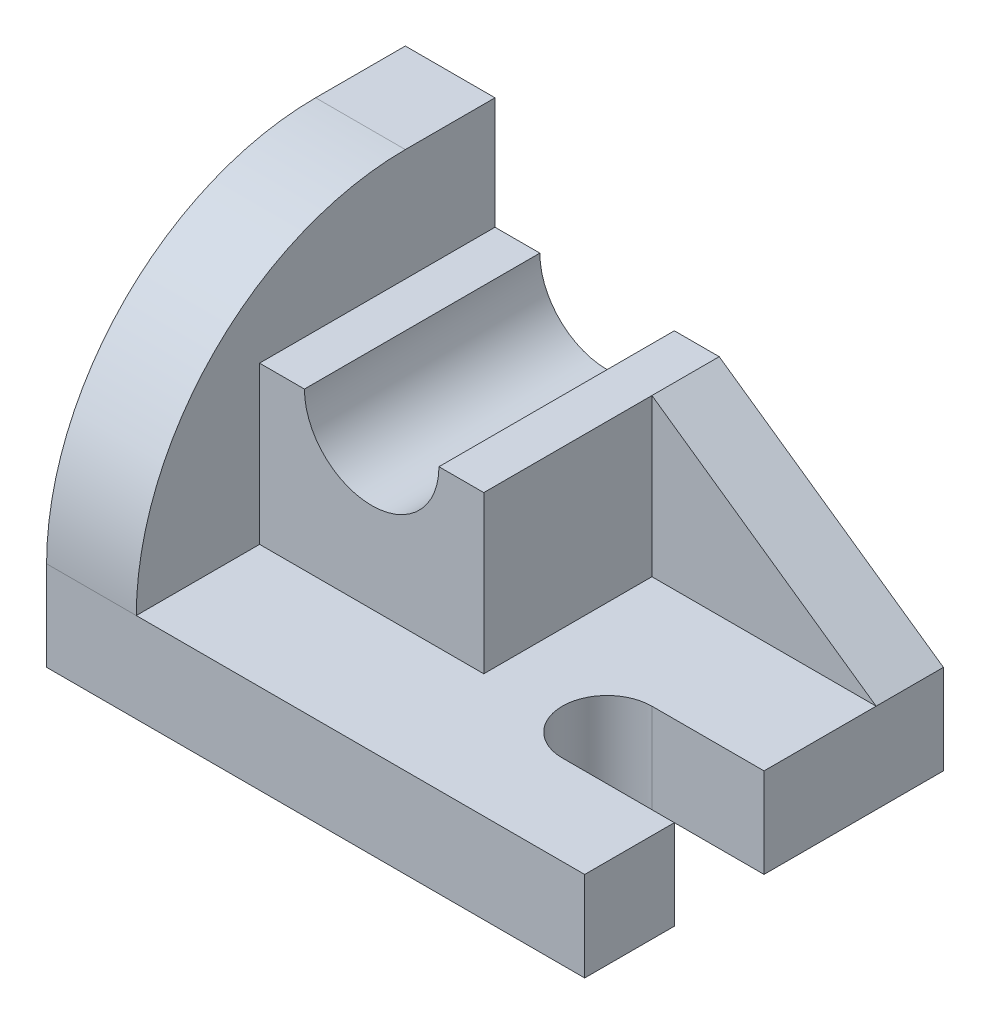
SolidWorks part; units mm, degrees
ref_plane "Front Plane" through (0, 0, 0) normal (0, 0, 1) x (1, 0, 0)
ref_plane "Top Plane" through (0, 0, 0) normal (0, 1, 0) x (1, 0, 0)
ref_plane "Right Plane" through (0, 0, 0) normal (1, 0, 0) x (0, 0, -1)
sketch "Sketch1" plane through (0, 0, 0) normal (0, 1, 0) x (1, 0, 0)
  line L1 (-46.7573, 25.6311) -> (49.2427, 25.6311)
  line L2 (-46.7573, 25.6311) -> (-46.7573, -38.3689)
  line L3 (-46.7573, -38.3689) -> (49.2427, -38.3689)
  line L4 (49.2427, 25.6311) -> (49.2427, -38.3689)
  dimension "D1" = 96
  dimension "D2" = 64
extrude "Boss-Extrude1" add sketch "Sketch1" along normal blind 16
sketch "Sketch2" plane through (0, 16, 0) normal (0, 1, 0) x (1, 0, 0)
  line L0 (-46.7573, -38.3689) -> (49.2427, -38.3689) construction
  line L1 (-46.7573, 25.6311) -> (-30.7573, 25.6311)
  line L2 (-46.7573, 25.6311) -> (-46.7573, -38.3689)
  line L3 (-46.7573, -38.3689) -> (-30.7573, -38.3689)
  line L4 (-30.7573, 25.6311) -> (-30.7573, -38.3689)
  dimension "D1" = 16
extrude "Boss-Extrude2" add sketch "Sketch2" along normal blind 48
fillet "Fillet1" radius 48 1 edges at (-38.7573, 64, 38.3689)
sketch "Sketch3" plane through (0, 16, 0) normal (0, 1, 0) x (1, 0, 0)
  line L0 (49.2427, -6.3689) -> (29.2427, -6.3689)
  line L1 (49.2427, -38.3689) -> (49.2427, 25.6311) construction
  line L2 (49.2427, -22.3689) -> (29.2427, -22.3689)
  line L4 (49.2427, -6.3689) -> (49.2427, -22.3689)
  arc A0 (29.2427, -6.3689) -> (29.2427, -22.3689) centre (29.2427, -14.3689) ccw
extrude "Cut-Extrude3" cut sketch "Sketch3" against normal blind 16
sketch "Sketch4" plane through (0, 16, 0) normal (0, 1, 0) x (1, 0, 0)
  line L0 (-30.7573, -38.3689) -> (49.2427, -38.3689) construction
  line L1 (-30.7573, 25.6311) -> (9.2427, 25.6311)
  line L2 (-30.7573, 25.6311) -> (-30.7573, -16.3689)
  line L3 (-30.7573, -16.3689) -> (9.2427, -16.3689)
  line L4 (9.2427, 25.6311) -> (9.2427, -16.3689)
  dimension "D1" = 22
  dimension "D2" = 40
extrude "Boss-Extrude3" add sketch "Sketch4" along normal blind 28
sketch "Sketch6" plane through (0, 0, 0) normal (0, 0, 1) x (1, 0, 0)
  line L0 (-30.7573, 44) -> (9.2427, 44) construction
  circle A0 centre (-10.7573, 44) radius 12
  dimension "D1" = 24
extrude "Cut-Extrude5" cut sketch "Sketch6" against normal through all both and the other way through all
sketch "Sketch10" plane through (0, 0, 0) normal (0, 1, 0) x (1, 0, 0)
  line L0 (9.2427, -16.3689) -> (9.2427, 25.6311) construction
  line L1 (49.2427, 25.6311) -> (9.2427, 25.6311)
  line L2 (49.2427, 25.6311) -> (49.2427, 13.6311)
  line L3 (49.2427, 13.6311) -> (9.2427, 13.6311)
  line L4 (9.2427, 25.6311) -> (9.2427, 13.6311)
  dimension "D1" = 12
extrude "Boss-Extrude4" add sketch "Sketch10" along normal blind 44
sketch "Sketch11" plane through (0, 0, -13.6311) normal (0, 0, 1) x (1, 0, 0)
  line L0 (9.2427, 44) -> (49.2427, 16)
  line L1 (9.2427, 44) -> (49.2427, 44)
  line L2 (49.2427, 44) -> (49.2427, 16)
extrude "Cut-Extrude6" cut sketch "Sketch11" against normal blind 44
